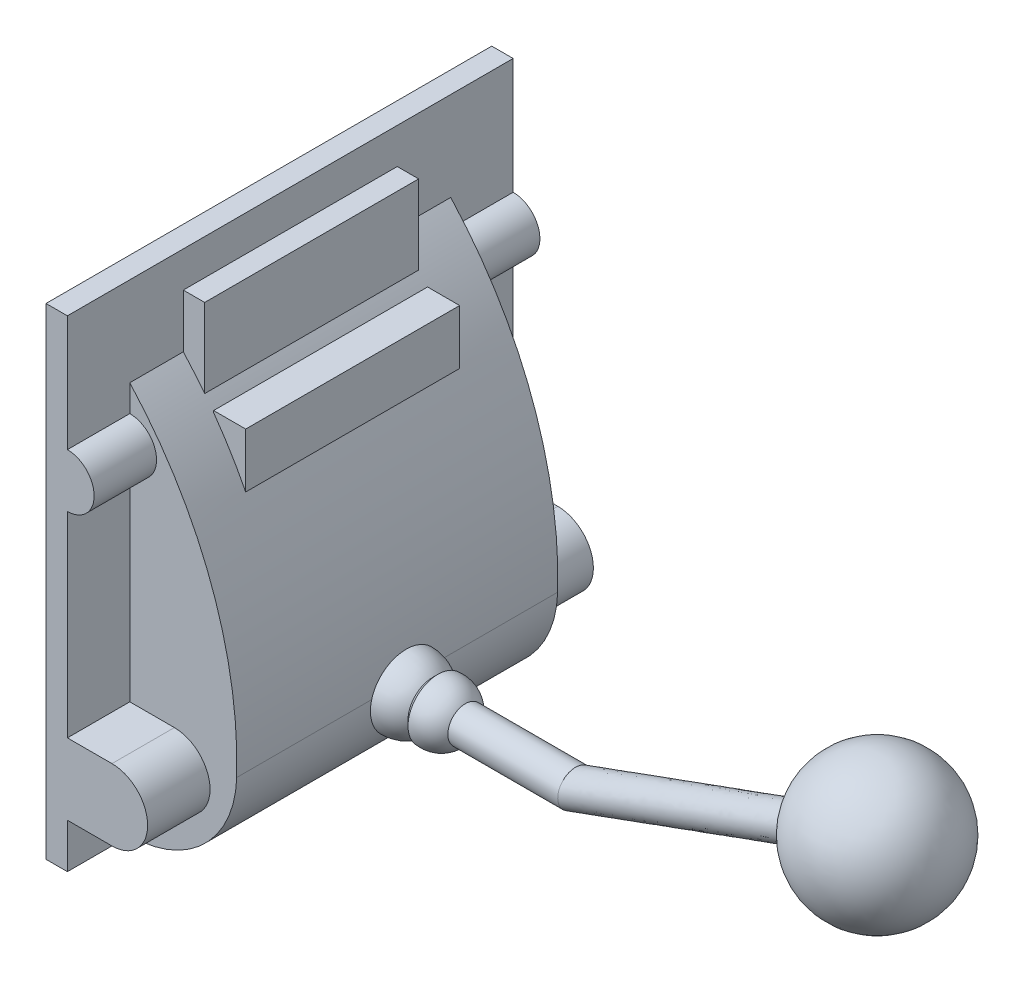
SolidWorks part; units mm, degrees
ref_plane "Front Plane" through (0, 0, 0) normal (0, 0, 1) x (1, 0, 0)
ref_plane "Top Plane" through (0, 0, 0) normal (0, 1, 0) x (1, 0, 0)
ref_plane "Right Plane" through (0, 0, 0) normal (1, 0, 0) x (0, 0, -1)
sketch "Sketch1" plane through (0, 0, 0) normal (0, 0, 1) x (1, 0, 0)
  line L0 (0, 0) -> (0, 220)
  arc A0 (0, 0) -> (59.974, 58.2353) centre (0, 60) ccw
  arc A1 (59.974, 58.2353) -> (0, 220) centre (-169.9265, 65) ccw
  dimension "D2" = 60
  dimension "D3" = 230
  dimension "D1" = 220
extrude "Boss-Extrude2" add sketch "Sketch1" along normal mid plane 180
sketch "Sketch2" plane through (0, 0, 0) normal (-1, 0, 0) x (0, 0, 1)
  line L0 (0, 0) -> (125, 0)
  line L1 (125, 0) -> (125, 270)
  line L2 (125, 270) -> (-125, 270)
  line L3 (-125, 270) -> (-125, 0)
  line L4 (-125, 0) -> (0, 0)
  dimension "D1" = 125
  dimension "D2" = 125
  dimension "D3" = 270
extrude "Boss-Extrude3" add sketch "Sketch2" along normal blind 12
sketch "Sketch3" plane through (0, 0, 0) normal (0, 0, 1) x (1, 0, 0)
  line L5 (17, 200) -> (35, 200)
  line L6 (17, 200) -> (17, 123.0184)
  line L7 (17, 123.0184) -> (35, 123.0184)
  line L8 (35, 200) -> (35, 123.0184)
  line L9 (0, 0) -> (0, 270) construction
  line L10 (0, 250) -> (12, 250)
  line L11 (0, 250) -> (0, 173.7446)
  line L12 (0, 173.7446) -> (12, 173.7446)
  line L13 (12, 250) -> (12, 173.7446)
  line L14 (0, 220) -> (0, 0) construction
  dimension "D1" = 12
  dimension "D2" = 30
  dimension "D3" = 18
  dimension "D4" = 90
  dimension "D5" = 35
  dimension "D6" = 50
extrude "Boss-Extrude4" add sketch "Sketch3" along normal mid plane 120
sketch "Sketch4" plane through (0, 0, 125) normal (0, 0, 1) x (1, 0, 0)
  line L0 (0, 0) -> (0, 270) construction
  line L1 (0, 65) -> (25, 65)
  line L2 (0, 65) -> (0, 25)
  line L3 (0, 25) -> (25, 25)
  line L4 (25, 65) -> (25, 25) construction
  line L5 (-12, 0) -> (0, 0) construction
  line L6 (0, 220) -> (0, 0) construction
  line L7 (0, 205) -> (0, 175)
  line L8 (12, 250) -> (0, 250) construction
  arc A0 (25, 25) -> (25, 65) centre (25, 45) ccw
  arc A1 (0, 175) -> (0, 205) centre (0, 190) ccw
  point P6 (0, 45)
  dimension "D3" = 20
  dimension "D5" = 30
  dimension "D1" = 45
  dimension "D2" = 40
  dimension "D4" = 25
  dimension "D6" = 60
extrude "Boss-Extrude5" add sketch "Sketch4" against normal through all
sketch "Sketch5" plane through (0, 0, 0) normal (1, 0, 0) x (0, 0, -1)
  line L0 (-90, 58.2353) -> (90, 58.2353) construction
  circle A0 centre (0, 58.2353) radius 10
  dimension "D1" = 20
extrude "Boss-Extrude6" add sketch "Sketch5" along normal blind 160
ref_plane "Plane1" through (0, 58, 0) normal (0, 1, 0) x (1, 0, 0)
sketch "Sketch6" plane through (0, 58, 0) normal (0, 1, 0) x (1, 0, 0)
  line L5 (81.6746, 0) -> (101.6746, 0)
  line L6 (82.7928, 16.7657) -> (79.8837, 13.8567)
  line L7 (64.974, 20.0325) -> (64.974, 0)
  line L8 (64.974, 0) -> (81.6746, 0)
  line L9 (59.974, 10) -> (59.974, 90) construction
  arc A2 (101.6746, 0) -> (82.7928, 16.7657) centre (84.7903, 0) ccw
  arc A3 (79.8837, 13.8567) -> (64.974, 20.0325) centre (64.974, -1.053) ccw
  dimension "D1" = 5
  dimension "D2" = 20
revolve "Revolve2" add sketch "Sketch6" angle 360 about L8
sketch "Sketch7" plane through (0, 0, 0) normal (0, 0, 1) x (1, 0, 0)
  line L0 (160, 58.2353) -> (329.1447, 119.7989)
  line L1 (160, 48.2353) -> (160, 68.2353) construction
  line L2 (160, 68.2353) -> (98.2186, 68.2353) construction
  dimension "D1" = 180
  dimension "D2" = 160
sketch "Sketch8" plane through (160, 0, 0) normal (1, 0, 0) x (0, 0, -1)
  circle A0 centre (0, 58.2353) radius 10
  dimension "D1" = 20
sweep "Sweep1" add profiles "Sketch8" path "Sketch7"
sketch "Sketch9" plane through (0, 0, 0) normal (0, 0, 1) x (1, 0, 0)
  line L0 (329.1447, 119.7989) -> (329.1447, 79.7989)
  line L1 (329.1447, 109.7989) -> (329.1447, 129.7989) construction
  line L2 (329.1447, 119.7989) -> (329.1447, 159.7989)
  arc A0 (329.1447, 159.7989) -> (329.1447, 79.7989) centre (329.1447, 119.7989) cw
  dimension "D1" = 40
  dimension "D2" = 40
revolve "Revolve3" add sketch "Sketch9" angle 360 about L0
